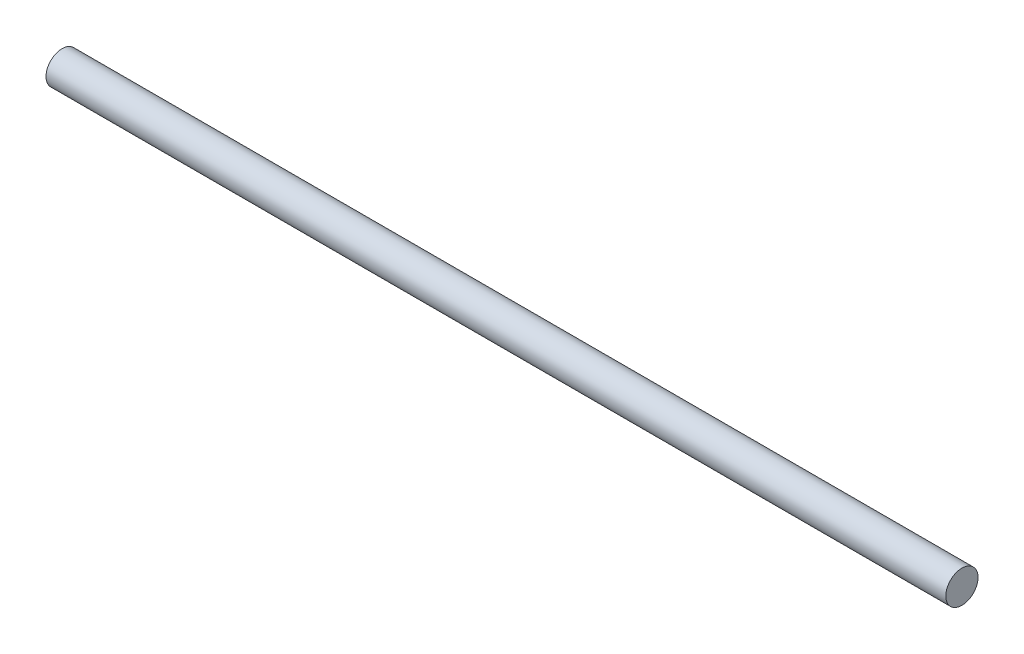
SolidWorks part; units mm, degrees
ref_plane "Front Plane" through (0, 0, 0) normal (0, 0, 1) x (1, 0, 0)
ref_plane "Top Plane" through (0, 0, 0) normal (0, 1, 0) x (1, 0, 0)
ref_plane "Right Plane" through (0, 0, 0) normal (1, 0, 0) x (0, 0, -1)
sketch "Sketch1" plane through (0, 0, 0) normal (1, 0, 0) x (0, 0, -1)
  circle A0 centre (0, 0) radius 5.461
  dimension "D1" = 10.922
extrude "Boss-Extrude1" add sketch "Sketch1" along normal blind 304.8
